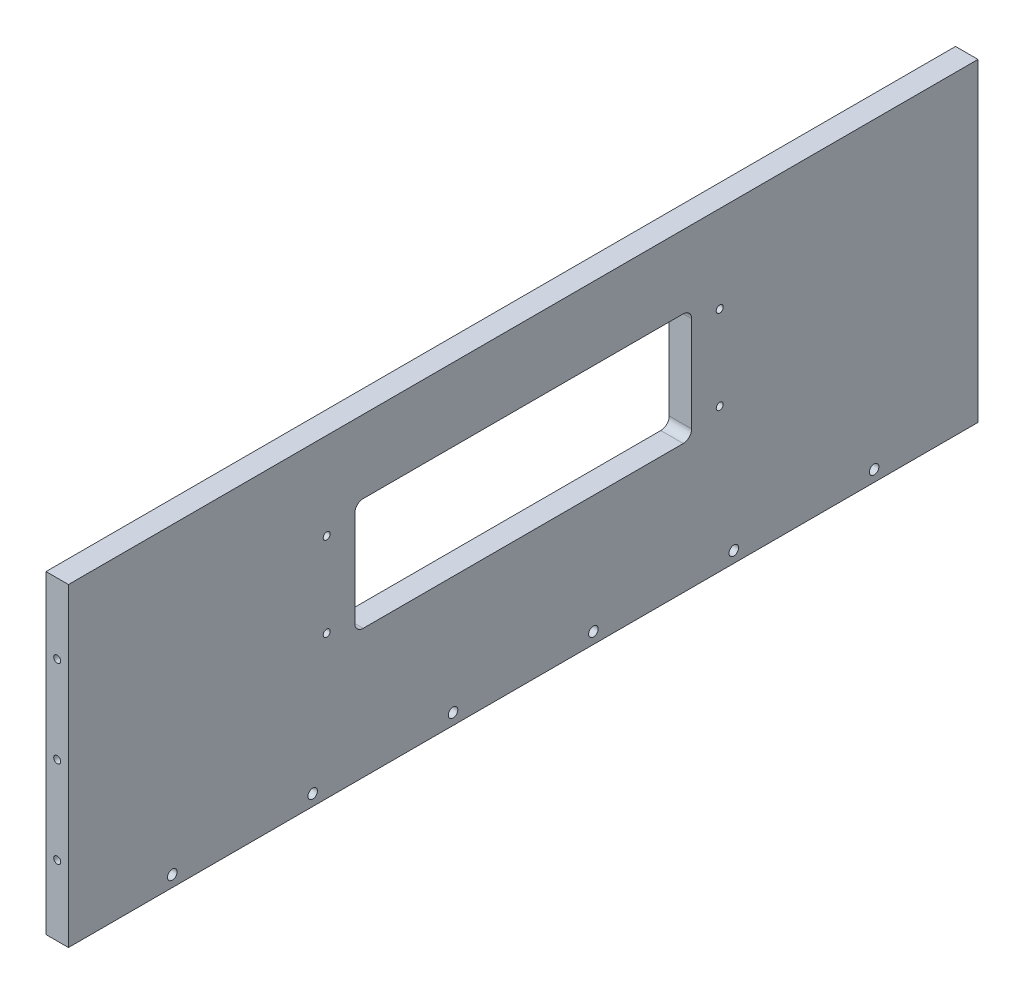
SolidWorks part; units mm, degrees
ref_plane "Front Plane" through (0, 0, 0) normal (0, 0, 1) x (1, 0, 0)
ref_plane "Top Plane" through (0, 0, 0) normal (0, 1, 0) x (1, 0, 0)
ref_plane "Right Plane" through (0, 0, 0) normal (1, 0, 0) x (0, 0, -1)
sketch "Sketch1" plane through (0, 0, 0) normal (1, 0, 0) x (0, 0, -1)
  line L1 (162, -56) -> (-162, -56)
  line L2 (162, -56) -> (162, 56)
  line L3 (162, 56) -> (-162, 56)
  line L4 (-162, -56) -> (-162, 56)
  line L5 (162, -56) -> (-162, 56) construction
  line L6 (162, 56) -> (-162, -56) construction
  point P0 (0, 0)
  dimension "D1" = 324
  dimension "D2" = 112
extrude "Boss-Extrude1" add sketch "Sketch1" along normal blind 8
sketch "Sketch2" plane through (0, 0, 162) normal (0, 0, 1) x (1, 0, 0)
  point P0 (4, -31)
  point P2 (4, 0)
  point P4 (4, 31)
hole_wizard "M3x0.5 Tapped Hole1" positions "3DSketch1" profile "Sketch4" tap size "M3x0.5" standard "BSI"
sketch3d "3DSketch1"
  point P0 (4, 31, 162)
  point P3 (4, 0, 162)
  point P6 (4, -31, 162)
sketch "Sketch4" plane through (4, 31, 162) normal (1, 0, 0) x (0, -1, 0)
  line L0 (0, 0) -> (0, 12.2511)
  line L1 (0, 12.2511) -> (1.25, 11.5)
  line L2 (1.25, 11.5) -> (1.25, 0)
  line L5 (1.25, 0) -> (0, 0)
  line L10 (0, 12.2511) -> (-1.25, 11.5) construction
  line L11 (0, -6.35) -> (0, 107.95) construction
  dimension "Tap Drill Dia." = 2.5
  dimension "Tap Drill Depth" = 11.5
  dimension "Drill Angle" = 118
cosmetic thread "Hole Thread4" parameters "D1"=10, "D2"=3
cosmetic thread "Hole Thread5" parameters "D1"=10, "D2"=3
cosmetic thread "Hole Thread6" parameters "D1"=10, "D2"=3
mirror "Mirror1" about plane through (0, 0, 0) normal (0, 0, 1) of "M3x0.5 Tapped Hole1"
sketch "Sketch5" plane through (0, 0, 0) normal (-1, 0, 0) x (0, 0, 1)
  line L0 (-162, -52) -> (162, -52) construction
  line L1 (-162, -56) -> (-162, 56) construction
  line L2 (162, 56) -> (162, -56) construction
  line L3 (162, -56) -> (-162, -56) construction
  line L4 (0, -52) -> (0, -56) construction
  point P8 (-125, -52)
  point P9 (-25, -52)
  point P12 (-75, -52)
  point P13 (25, -52)
  point P14 (75, -52)
  point P17 (125, -52)
  dimension "D1" = 4
  dimension "D2" = 50
  dimension "D3" = 25
  dimension "D4" = 50
hole_wizard "CSK for M3 Countersunk Flat Head1" positions "3DSketch2" profile "Sketch7" countersink size "M3" standard "BSI"
sketch3d "3DSketch2"
  point P0 (0, -52, -125)
  point P3 (0, -52, -75)
  point P6 (0, -52, -25)
  point P9 (0, -52, 25)
  point P12 (0, -52, 75)
  point P15 (0, -52, 125)
sketch "Sketch7" plane through (0, -52, -125) normal (0, 1, 0) x (0, 0, 1)
  line L0 (0, 0) -> (0, 12.5215)
  line L1 (0, 12.5215) -> (1.7, 11.5)
  line L2 (1.7, 11.5) -> (1.7, 1.45)
  line L3 (1.7, 1.45) -> (3.15, 0)
  line L5 (3.15, 0) -> (0, 0)
  line L6 (-1.7, 1.45) -> (-3.15, 0) construction
  line L10 (0, 12.5215) -> (-1.7, 11.5) construction
  line L11 (0, -6.35) -> (0, 107.95) construction
  dimension "Hole Dia." = 3.4
  dimension "Hole Depth" = 11.5
  dimension "Near C'Sink Dia." = 6.3
  dimension "Near C'Sink Angle" = 90
  dimension "Drill Angle" = 118
sketch "Sketch8" plane through (8, 0, 0) normal (1, 0, 0) x (0, 0, -1)
  line L0 (0, -56) -> (0, 4) construction
  line L1 (-162, -56) -> (162, -56) construction
  line L2 (0, 4) -> (65, 4) construction
  point P7 (65, 4)
  dimension "D1" = 60
  dimension "D2" = 130
sketch "Sketch9" plane through (8, 0, 0) normal (1, 0, 0) x (0, 0, -1)
  line L1 (60, -10) -> (-60, -10)
  line L2 (60, -10) -> (60, 30)
  line L3 (60, 30) -> (-60, 30)
  line L4 (-60, -10) -> (-60, 30)
  line L5 (60, -10) -> (-60, 30) construction
  line L6 (60, 30) -> (-60, -10) construction
  point P0 (0, 10)
  dimension "D1" = 10
  dimension "D2" = 40
  dimension "D3" = 120
extrude "Cut-Extrude1" cut sketch "Sketch9" against normal through all
sketch "Sketch10" plane through (8, 0, 0) normal (1, 0, 0) x (0, 0, -1)
  line L0 (-60, 30) -> (-60, -10) construction
  line L1 (60, 30) -> (-60, 30) construction
  line L2 (-60, -10) -> (60, -10) construction
  point P0 (-70, 25)
  point P1 (-70, -5)
  point P2 (0, 0)
  dimension "D1" = 10
  dimension "D2" = 5
  dimension "D3" = 5
hole_wizard "M3x0.5 Tapped Hole2" positions "3DSketch3" profile "Sketch11" tap size "M3x0.5" standard "ANSI Metric" end condition through all
sketch3d "3DSketch3"
  point P0 (8, 25, 70)
  point P3 (8, -5, 70)
sketch "Sketch11" plane through (8, 25, 70) normal (0, 1, 0) x (0, 0, -1)
  line L0 (0, 0) -> (0, 8)
  line L1 (0, 8) -> (1.25, 8)
  line L2 (1.25, 8) -> (1.25, 0)
  line L5 (1.25, 0) -> (0, 0)
  line L11 (0, -6.35) -> (0, 107.95) construction
  dimension "Thru Tap Drill Dia." = 2.5
  dimension "Thru Tap Drill Depth" = 8
cosmetic thread "Hole Thread7" parameters "D2"=3
cosmetic thread "Hole Thread8" parameters "D2"=3
mirror "Mirror2" about plane through (0, 0, 0) normal (0, 0, 1) of "M3x0.5 Tapped Hole2"
fillet "Fillet1" radius 3 4 edges at (4, -10, -60) (4, -10, 60) (4, 30, 60) (4, 30, -60)
